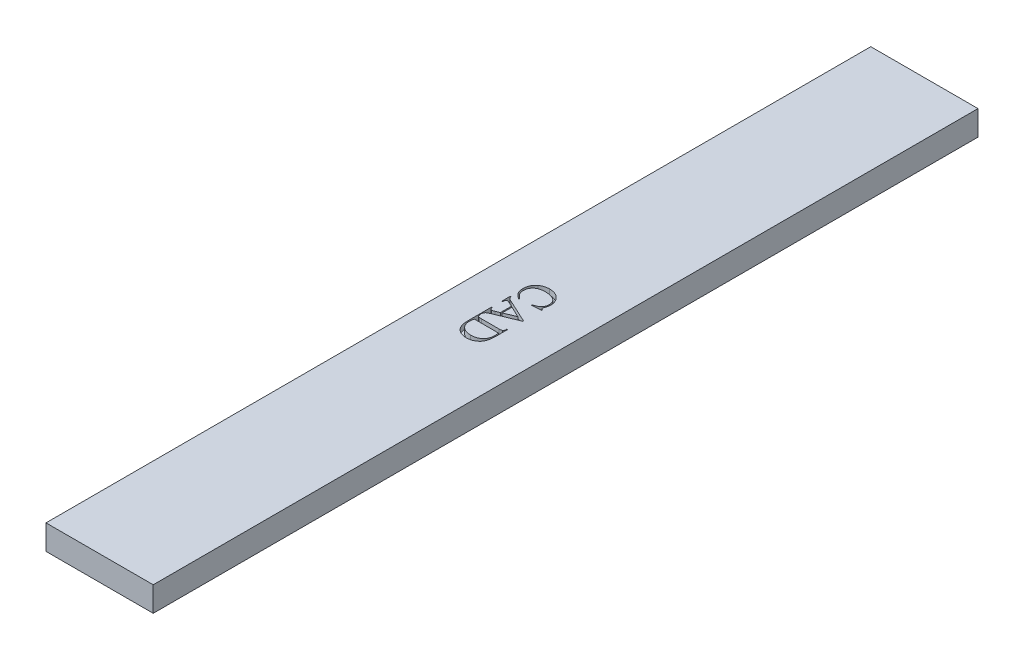
SolidWorks part; units mm, degrees
ref_plane "Front Plane" through (0, 0, 0) normal (0, 0, 1) x (1, 0, 0)
ref_plane "Top Plane" through (0, 0, 0) normal (0, 1, 0) x (1, 0, 0)
ref_plane "Right Plane" through (0, 0, 0) normal (1, 0, 0) x (0, 0, -1)
sketch "Sketch1" plane through (0, 0, 0) normal (0, 0, 1) x (1, 0, 0)
  line L1 (-9.75, 2.25) -> (9.75, 2.25)
  line L2 (-9.75, 2.25) -> (-9.75, -2.25)
  line L3 (-9.75, -2.25) -> (9.75, -2.25)
  line L4 (9.75, 2.25) -> (9.75, -2.25)
  line L5 (-9.75, 2.25) -> (9.75, -2.25) construction
  line L6 (-9.75, -2.25) -> (9.75, 2.25) construction
  point P0 (0, 0)
  dimension "D1" = 4.5
  dimension "D2" = 19.5
extrude "Boss-Extrude1" add sketch "Sketch1" along normal blind 150
sketch "Sketch2" plane through (0, 2.25, 0) normal (0, 1, 0) x (1, 0, 0)
  line L0 (-3.2166, 0) -> (-3.2166, -150) construction
  line L1 (9.75, 0) -> (-9.75, 0) construction
  line L2 (9.75, -150) -> (-9.75, -150) construction
  text T0 "CAD" font "Times New Roman" height 5
extrude "Cut-Extrude1" cut sketch "Sketch2" against normal blind 1
